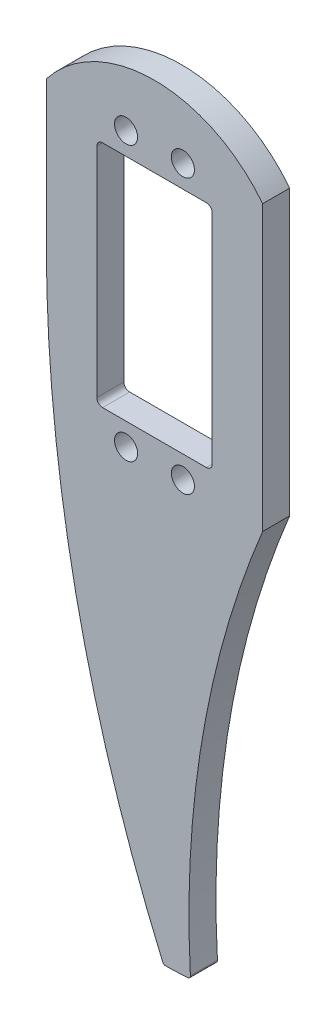
SolidWorks part; units mm, degrees
ref_plane "Front Plane" through (0, 0, 0) normal (0, 0, 1) x (1, 0, 0)
ref_plane "Top Plane" through (0, 0, 0) normal (0, 1, 0) x (1, 0, 0)
ref_plane "Right Plane" through (0, 0, 0) normal (1, 0, 0) x (0, 0, -1)
sketch "Sketch1" plane through (0, 0, 0) normal (0, 0, 1) x (1, 0, 0)
  line L0 (0, -49.992) -> (0, 0)
  line L1 (-38.1, 0) -> (-38.1, -24.996)
  line L2 (-12.7, -124.6272) -> (-13.636, -108.4396) construction
  line L3 (0, -49.992) -> (-38.1, 0) construction
  line L5 (-29.21, -4.803) -> (-8.89, -4.803)
  line L6 (-29.21, -4.803) -> (-29.21, -45.189)
  line L7 (-29.21, -45.189) -> (-8.89, -45.189)
  line L8 (-8.89, -4.803) -> (-8.89, -45.189)
  line L9 (-29.21, -4.803) -> (-8.89, -45.189) construction
  line L10 (-29.21, -45.189) -> (-8.89, -4.803) construction
  line L11 (-19.05, -24.996) -> (-19.05, 38.1894) construction
  line L12 (-19.05, -24.996) -> (22.2854, -24.996) construction
  arc A0 (0, 0) -> (-38.1, 0) centre (-19.05, -14.8106) ccw
  circle A1 centre (-14.0462, -0.866) radius 2.032
  circle A2 centre (-24.0538, -0.866) radius 2.032
  circle A3 centre (-24.0538, -49.126) radius 2.032
  circle A4 centre (-14.0462, -49.126) radius 2.032
  arc A5 (-17.4594, -124.7991) -> (-12.7, -124.6272) centre (-19.05, -14.8106) ccw
  arc A6 (-38.1, -24.996) -> (-17.4594, -124.7991) centre (213.5083, -24.996) ccw
  arc A7 (-12.7, -124.6272) -> (0, -49.992) centre (155.7239, -114.8883) cw
  point P5 (-19.05, -24.996)
  point P6 (-19.05, -24.996)
  point P13 (-19.05, -14.8106)
  dimension "D8" = 4.064
  dimension "D4" = 24.13
  dimension "D11" = 110
  dimension "D2" = 4.7625
  dimension "D3" = 38.1
  dimension "D5" = 40.386
  dimension "D6" = 20.32
  dimension "D7" = 5.0038
  dimension "D9" = 10.0076
  dimension "D10" = 48.26
  dimension "D12" = 12.7
extrude "Boss-Extrude1" add sketch "Sketch1" along normal blind 4.7625
fillet "Fillet1" radius 1.016 4 edges at (-29.21, -45.189, 2.3813) (-8.89, -45.189, 2.3813) (-29.21, -4.803, 2.3813) (-8.89, -4.803, 2.3813)
fillet "Fillet2" radius 0.508 2 edges at (-12.7, -124.6272, 2.3813) (-17.4594, -124.7991, 2.3813)
